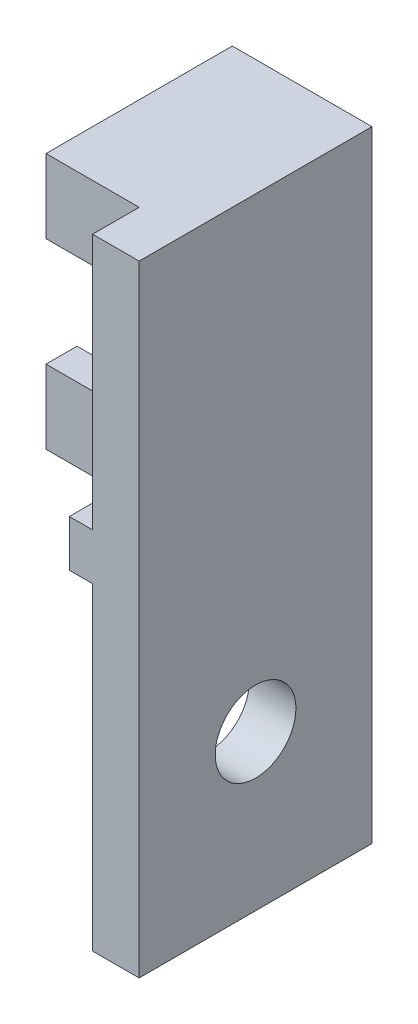
SolidWorks part; units mm, degrees
ref_plane "Front Plane" through (0, 0, 0) normal (0, 0, 1) x (1, 0, 0)
ref_plane "Top Plane" through (0, 0, 0) normal (0, 1, 0) x (1, 0, 0)
ref_plane "Right Plane" through (0, 0, 0) normal (1, 0, 0) x (0, 0, -1)
sketch "Sketch1" plane through (0, 0, 0) normal (1, 0, 0) x (0, 0, -1)
  line L0 (0, 10) -> (15, 10) construction
  line L1 (0, 0) -> (15, 0)
  line L2 (0, 0) -> (0, 40)
  line L3 (0, 40) -> (15, 40)
  line L4 (15, 0) -> (15, 40)
  circle A0 centre (7.5, 10) radius 2.6
  dimension "D4" = 5.2
  dimension "D1" = 40
  dimension "D2" = 15
  dimension "D3" = 10
extrude "Boss-Extrude1" add sketch "Sketch1" along normal blind 3
sketch "Sketch2" plane through (0, 0, 0) normal (-1, 0, 0) x (0, 0, 1)
  line L0 (-15, 0) -> (-15, 40) construction
  line L1 (-15, 23.5) -> (0, 23.5)
  line L2 (-15, 23.5) -> (-15, 20.5)
  line L3 (-15, 20.5) -> (0, 20.5)
  line L4 (0, 23.5) -> (0, 20.5)
  line L5 (0, 0) -> (-15, 0) construction
  dimension "D1" = 20.5
  dimension "D2" = 3
extrude "Boss-Extrude2" add sketch "Sketch2" along normal blind 1.5
sketch "Sketch3" plane through (0, 0, 0) normal (-1, 0, 0) x (0, 0, 1)
  line L0 (-15, 25) -> (-5, 25)
  line L1 (-15, 23.5) -> (-15, 40) construction
  line L2 (-5, 25) -> (-5, 38.5)
  line L3 (-5, 38.5) -> (-15, 38.5)
  line L4 (-15, 38.5) -> (-15, 40)
  line L5 (-15, 40) -> (-3, 40)
  line L7 (-15, 40) -> (0, 40) construction
  line L8 (-3, 40) -> (-3, 23.5)
  line L9 (-15, 23.5) -> (-15, 25)
  line L10 (0, 23.5) -> (-15, 23.5) construction
  line L11 (-3, 23.5) -> (-15, 23.5)
  dimension "D1" = 13.5
  dimension "D2" = 12
  dimension "D3" = 10
extrude "Boss-Extrude3" add sketch "Sketch3" along normal blind 6
sketch "Sketch4" plane through (-6, 0, 0) normal (-1, 0, 0) x (0, 0, 1)
  line L0 (-3, 31.75) -> (-5, 31.75) construction
  line L1 (-3, 23.5) -> (-3, 40) construction
  line L2 (-5, 38.5) -> (-5, 25) construction
  line L4 (-3, 35.25) -> (-5, 35.25)
  line L5 (-3, 35.25) -> (-3, 28.25)
  line L6 (-3, 28.25) -> (-5, 28.25)
  line L7 (-5, 35.25) -> (-5, 28.25)
  line L8 (-3, 35.25) -> (-5, 28.25) construction
  line L9 (-3, 28.25) -> (-5, 35.25) construction
  point P6 (-4, 31.75)
  dimension "D1" = 7
extrude "Cut-Extrude1" cut sketch "Sketch4" against normal blind 6
